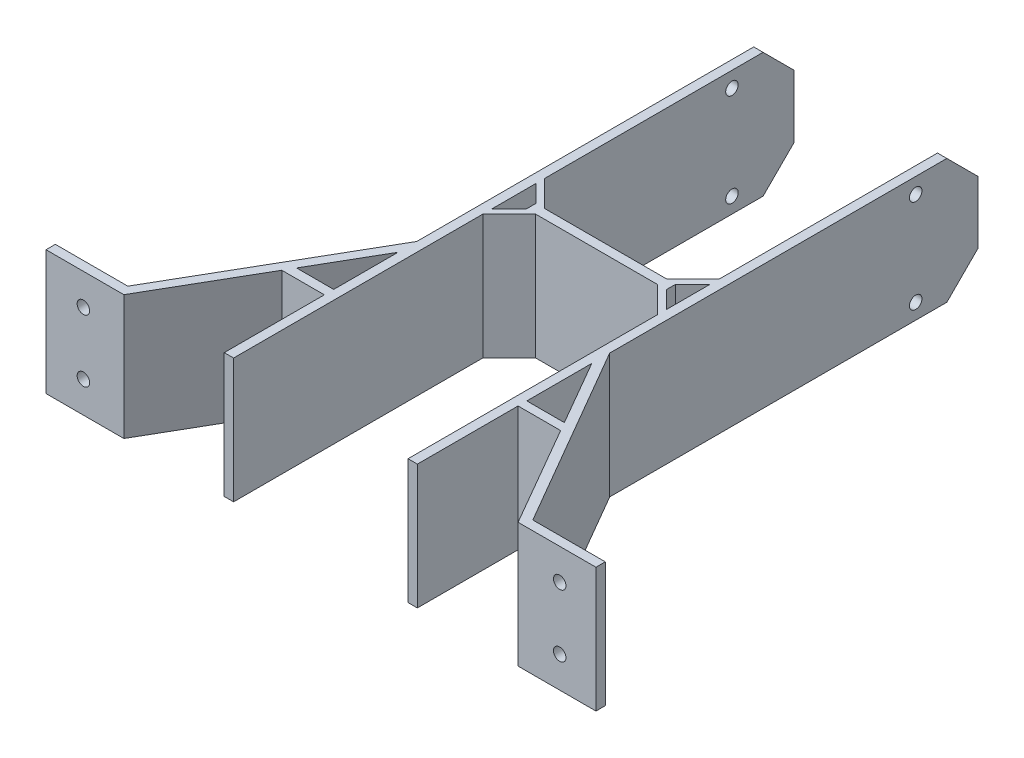
SolidWorks part; units mm, degrees
ref_plane "Alzado" through (0, 0, 0) normal (0, 0, 1) x (1, 0, 0)
ref_plane "Planta" through (0, 0, 0) normal (0, 1, 0) x (1, 0, 0)
ref_plane "Vista lateral" through (0, 0, 0) normal (1, 0, 0) x (0, 0, -1)
sketch "Croquis1" plane through (0, 0, 0) normal (0, 1, 0) x (1, 0, 0)
  line L0 (-32.5, 0) -> (32.5, 0) construction
  line L1 (-28, 9.8655) -> (-19.6345, 1.5)
  line L2 (-28, -90) -> (-31, -90)
  line L3 (-28, -90) -> (-28, -9.8655)
  line L4 (-28, 90) -> (-31, 90)
  line L5 (-31, -90) -> (-31, -57.8568)
  line L6 (-28, -90) -> (-31, 90) construction
  line L7 (-28, 90) -> (-31, -90) construction
  line L8 (31, -90) -> (28, -90)
  line L9 (31, -90) -> (31, -57.6674)
  line L10 (31, 90) -> (28, 90)
  line L11 (28, -90) -> (28, -9.8655)
  line L12 (31, -90) -> (28, 90) construction
  line L13 (31, 90) -> (28, -90) construction
  line L14 (-19.6345, 1.5) -> (19.6345, 1.5)
  line L15 (19.6345, 1.5) -> (28, 9.8655)
  line L16 (-28, -9.8655) -> (-19.6345, -1.5)
  line L17 (-19.6345, -1.5) -> (19.6345, -1.5)
  line L18 (19.6345, -1.5) -> (28, -9.8655)
  line L19 (0, 1.5) -> (0, -1.5) construction
  line L20 (-28, -7.037) -> (-22.455, -1.492)
  line L21 (-22.455, -1.492) -> (-22.455, 1.492)
  line L22 (-22.455, 1.492) -> (-28, 7.037)
  line L23 (28, -7.0117) -> (22.455, -1.4667)
  line L24 (22.455, -1.4667) -> (22.455, 1.4667)
  line L25 (22.455, 1.4667) -> (28, 7.0117)
  line L26 (-28, 9.8655) -> (-28, 90)
  line L27 (-28, -7.037) -> (-28, 7.037)
  line L28 (28, -7.0117) -> (28, 7.0117)
  line L29 (28, 9.8655) -> (28, 90)
  line L30 (31, -33.9913) -> (43.0467, -54.8568)
  line L31 (63.3366, -90) -> (88.3366, -90)
  line L32 (88.3366, -90) -> (88.3366, -87)
  line L33 (88.3366, -87) -> (65.0687, -87)
  line L34 (65.0687, -87) -> (31, -28.2439)
  line L35 (-31, -34.1807) -> (-42.9373, -54.8568)
  line L36 (-63.2273, -90) -> (-88.2273, -90)
  line L37 (-88.2273, -90) -> (-88.2273, -87)
  line L38 (-88.2273, -87) -> (-64.9594, -87)
  line L39 (-64.9594, -87) -> (-31, -28.1807)
  line L40 (-44.6694, -57.8568) -> (-31, -57.8568)
  line L41 (-42.9373, -54.8568) -> (-31, -54.8568)
  line L42 (44.6694, -57.6674) -> (31, -57.6674)
  line L43 (43.0467, -54.8568) -> (31, -54.8568)
  line L44 (-44.6694, -57.8568) -> (-63.2273, -90)
  line L45 (-31, -54.8568) -> (-31, -34.1807)
  line L46 (-31, -28.1807) -> (-31, 90)
  line L47 (44.6694, -57.6674) -> (63.3366, -90)
  line L48 (31, -54.8568) -> (31, -33.9913)
  line L49 (31, -28.2439) -> (31, 90)
  point P3 (29.5, 0)
  point P4 (0, 0)
  point P7 (-29.5, 0)
  point P20 (0, 0)
  point P23 (0, 1.5)
  point P24 (0, -1.5)
  point P34 (22.455, 0)
  dimension "D1" = 3
  dimension "D2" = 56
  dimension "D3" = 3
  dimension "D4" = 2
  dimension "D5" = 2
  dimension "D6" = 180
  dimension "D7" = 60
  dimension "D8" = 60
  dimension "D9" = 3
  dimension "D10" = 3
  dimension "D11" = 3
  dimension "D12" = 25
extrude "Saliente-Extruir1" add sketch "Croquis1" along normal blind 40
sketch "Croquis2" plane through (31, 0, 0) normal (1, 0, 0) x (0, 0, -1)
  line L0 (90, 40) -> (90, 0) construction
  line L1 (70, 35) -> (70, 5) construction
  line L2 (-90, 40) -> (-57.6674, 40) construction
  circle A0 centre (70, 35) radius 2
  circle A1 centre (70, 5) radius 2
  point P4 (70, 20)
  dimension "D1" = 4
  dimension "D2" = 20
  dimension "D3" = 20
  dimension "D4" = 30
extrude "Cortar-Extruir1" cut sketch "Croquis2" against normal through all
chamfer "Chaflán1" distance 10 angle 45 4 edges at (-29.5, 40, -90) (-29.5, 0, -90) (29.5, 0, -90) (29.5, 40, -90)
sketch "Croquis3" plane through (0, 0, 87) normal (0, 0, -1) x (-1, 0, 0)
  line L1 (-88.3366, 40) -> (-65.0687, 40) construction
  line L2 (-88.3366, 0) -> (-65.0687, 0) construction
  line L3 (88.2273, 40) -> (88.2273, 0) construction
  circle A0 centre (-76.7027, 30) radius 2
  circle A1 centre (-76.7027, 10) radius 2
  circle A2 centre (76.2273, 30) radius 2
  circle A3 centre (76.2273, 10) radius 2
  point P12 (0, 0)
  point P13 (0, 0)
  point P14 (0, 0)
  point P15 (0, 0)
  point P16 (-76.7027, 40)
  point P17 (0, 0)
  point P18 (0, 0)
  point P19 (0, 0)
  point P20 (0, 0)
  point P23 (0, 0)
  dimension "D1" = 4
  dimension "D2" = 10
  dimension "D3" = 10
  dimension "D4" = 12
extrude "Cortar-Extruir2" cut sketch "Croquis3" against normal through all
